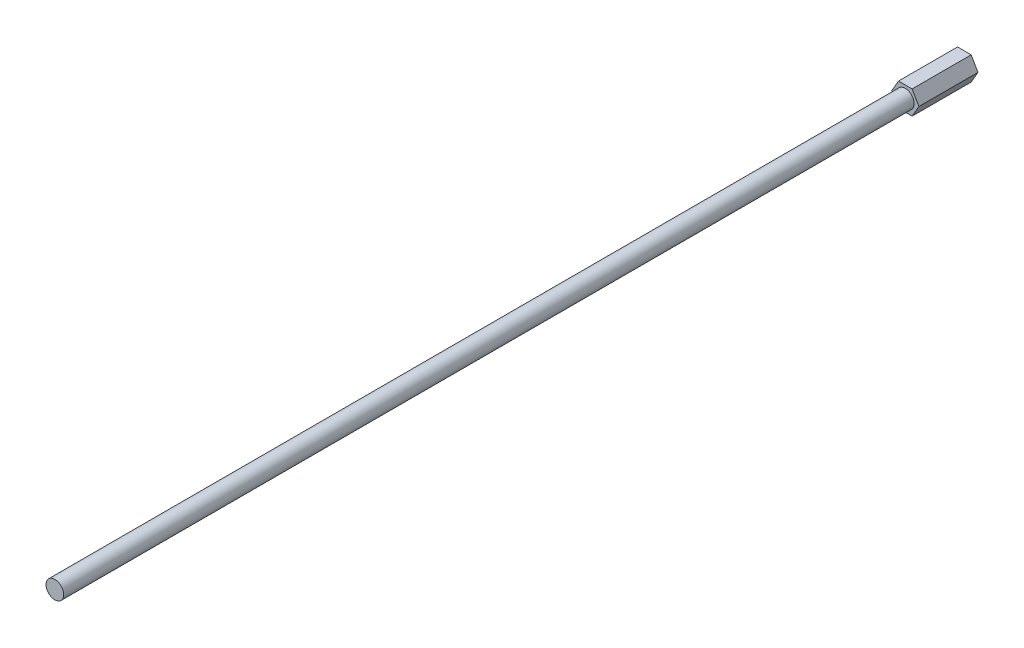
SolidWorks part; units mm, degrees
ref_plane "Front Plane" through (0, 0, 0) normal (0, 0, 1) x (1, 0, 0)
ref_plane "Top Plane" through (0, 0, 0) normal (0, 1, 0) x (1, 0, 0)
ref_plane "Right Plane" through (0, 0, 0) normal (1, 0, 0) x (0, 0, -1)
sketch "Sketch1" plane through (0, 0, 0) normal (0, 0, 1) x (1, 0, 0)
  line L1 (7.3323, 0) -> (3.6662, 6.35)
  line L2 (3.6662, 6.35) -> (-3.6662, 6.35)
  line L3 (-3.6662, 6.35) -> (-7.3323, 0)
  line L4 (-7.3323, 0) -> (-3.6662, -6.35)
  line L5 (-3.6662, -6.35) -> (3.6662, -6.35)
  line L6 (3.6662, -6.35) -> (7.3323, 0)
  circle A0 centre (0, 0) radius 6.35 construction
  dimension "D1" = 12.7
extrude "Boss-Extrude1" add sketch "Sketch1" along normal blind 31.75
sketch "Sketch2" plane through (0, 0, 31.75) normal (0, 0, 1) x (1, 0, 0)
  circle A0 centre (0, 0) radius 4.7625
  dimension "D1" = 9.525
extrude "Boss-Extrude2" add sketch "Sketch2" along normal blind 457.2
